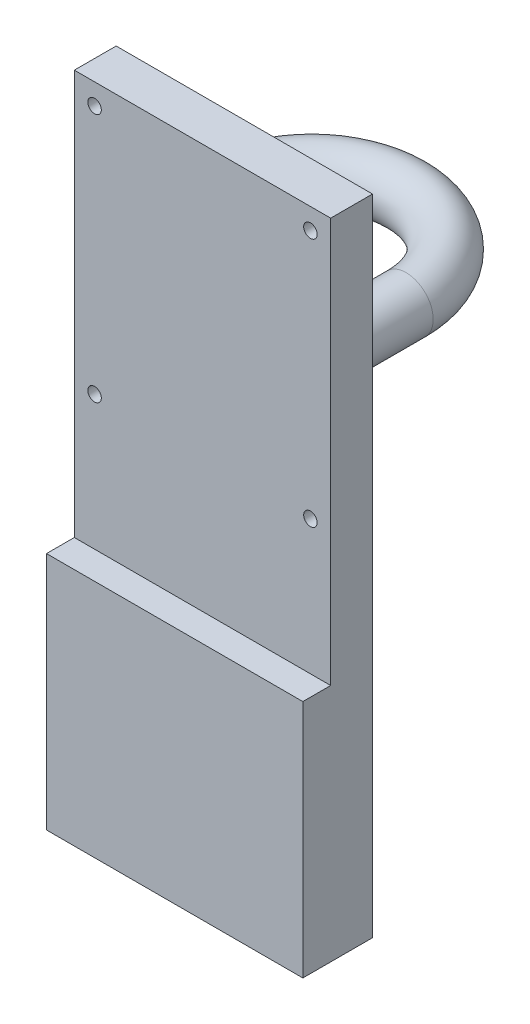
SolidWorks part; units mm, degrees
ref_plane "Plan de face" through (0, 0, 0) normal (0, 0, 1) x (1, 0, 0)
ref_plane "Plan de dessus" through (0, 0, 0) normal (0, 1, 0) x (1, 0, 0)
ref_plane "Plan de droite" through (0, 0, 0) normal (1, 0, 0) x (0, 0, -1)
sketch "Esquisse1" plane through (0, 0, 0) normal (0, 0, 1) x (1, 0, 0)
  line L1 (0, 0) -> (190, 0)
  line L2 (0, 0) -> (0, 300)
  line L3 (0, 300) -> (190, 300)
  line L4 (190, 0) -> (190, 300)
  dimension "D1" = 190
  dimension "D2" = 300
extrude "Boss.-Extru.1" add sketch "Esquisse1" along normal blind 31
sketch "Esquisse2" plane through (0, 0, 0) normal (0, 0, -1) x (-1, 0, 0)
  line L0 (-190, 300) -> (0, 300) construction
  line L3 (-190, 0) -> (-190, 300) construction
  line L4 (0, 300) -> (0, 0) construction
  line L5 (-1232.0432, 99.5) -> (48767.9568, 99.5) construction
  circle A0 centre (-175, 284.5) radius 5
  circle A1 centre (-15, 284.5) radius 5
  circle A2 centre (-175, 99.5) radius 5
  circle A3 centre (-15, 99.5) radius 5
  dimension "D1" = 10
  dimension "D4" = 10
  dimension "D8" = 10
  dimension "D9" = 10
  dimension "D2" = 15.5
  dimension "D3" = 15
  dimension "D5" = 15
  dimension "D6" = 15.5
  dimension "D7" = 200.5
  dimension "D10" = 15
  dimension "D11" = 15
extrude "Enlèv. mat.-Extru.1" cut sketch "Esquisse2" against normal through all
sketch "Esquisse3" plane through (0, 0, 0) normal (0, -1, 0) x (1, 0, 0)
  line L1 (0, 0) -> (190, 0)
  line L2 (0, 0) -> (0, 51.62)
  line L3 (0, 51.62) -> (190, 51.62)
  line L4 (190, 0) -> (190, 51.62)
  dimension "D1" = 190
  dimension "D2" = 51.62
extrude "Boss.-Extru.2" add sketch "Esquisse3" along normal blind 177.45
sketch "Esquisse4" plane through (0, 0, 0) normal (0, 0, -1) x (-1, 0, 0)
  line L0 (-190, -177.45) -> (0, 300) construction
  line L1 (-190, 300) -> (0, -177.45) construction
  line L3 (-95, -938.725) -> (-95, 49061.275) construction
  line L4 (-190, 300) -> (0, 300) construction
  circle A1 centre (-165, 192) radius 20
  point P11 (-95, 61.275)
  dimension "D1" = 70
  dimension "D3" = 40
  dimension "D2" = 108
extrude "Boss.-Extru.3" add sketch "Esquisse4" along normal blind 50 contours A1
ref_plane "Plan1" through (95, 0, 0) normal (1, 0, 0) x (0, 0, -1)
mirror "Symétrie1" about plane through (95, 0, 0) normal (1, 0, 0) of "Boss.-Extru.3"
ref_plane "Plan2" through (0, 0, -50) normal (0, 0, -1) x (-1, 0, 0)
ref_axis "Axe1" through (95, -201.3225, -50) along (0, 1, 0)
sketch "Esquisse6" plane through (0, 0, -50) normal (0, 0, -1) x (-1, 0, 0)
  circle A0 centre (-165, 192) radius 20
  dimension "D1" = 40
revolve "Révolution1" add sketch "Esquisse6" angle 180 about axis through (95, -201.3225, -50) along (0, 1, 0)
ref_plane "Plan3" through (0, 192, 0) normal (0, 1, 0) x (1, 0, 0)
equation "\"D7@Esquisse2\"=216-15.5"
equation "\"D2@Esquisse3\"=31+20.62"
